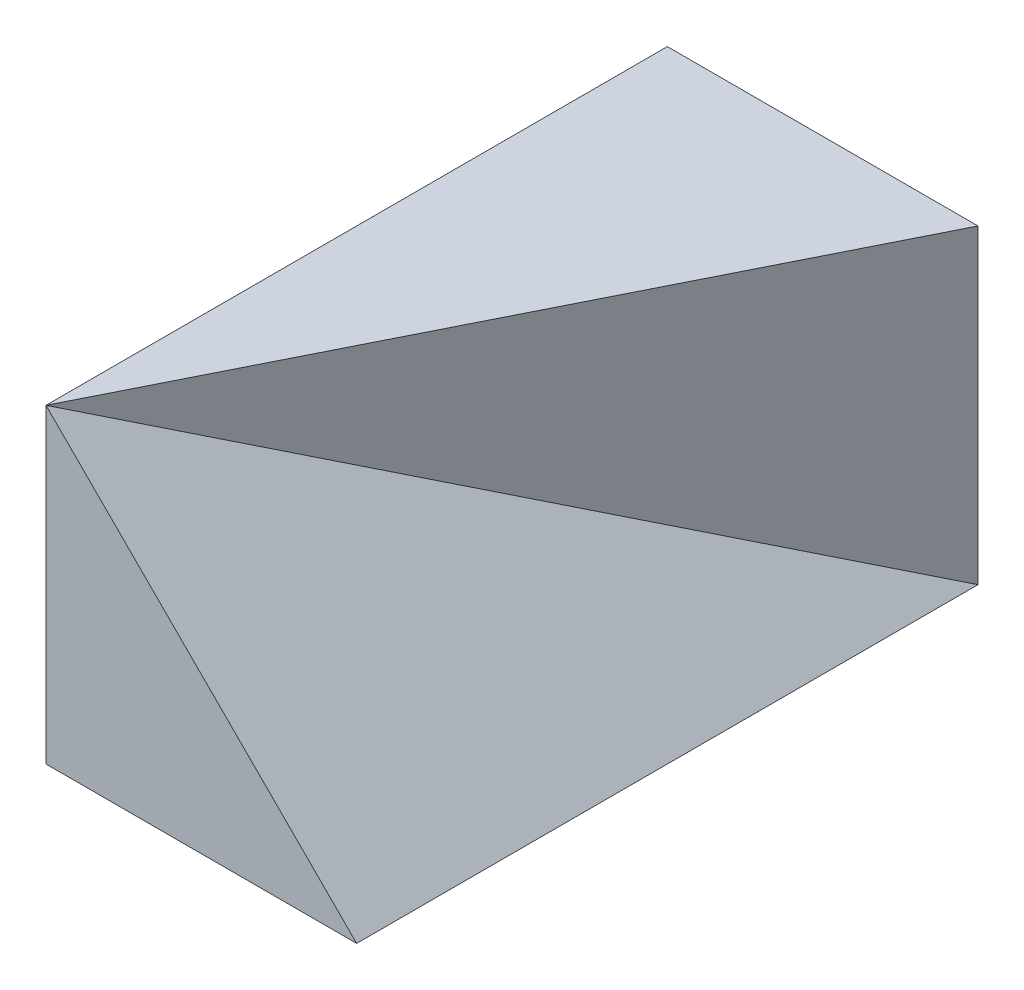
SolidWorks part; units mm, degrees
ref_plane "Front Plane" through (0, 0, 0) normal (0, 0, 1) x (1, 0, 0)
ref_plane "Top Plane" through (0, 0, 0) normal (0, 1, 0) x (1, 0, 0)
ref_plane "Right Plane" through (0, 0, 0) normal (1, 0, 0) x (0, 0, -1)
sketch "Sketch1" plane through (0, 0, 0) normal (0, 0, 1) x (1, 0, 0)
  line L1 (-25, -25) -> (25, -25)
  line L2 (-25, -25) -> (-25, 25)
  line L3 (-25, 25) -> (25, 25)
  line L4 (25, -25) -> (25, 25)
  line L5 (-25, -25) -> (25, 25) construction
  line L6 (-25, 25) -> (25, -25) construction
  point P0 (0, 0)
  dimension "D1" = 50
  dimension "D2" = 50
extrude "Boss-Extrude1" add sketch "Sketch1" along normal mid plane 100
sketch3d "3DSketch1"
  line L0 (-25, 25, 50) -> (25, -25, -50)
  line L1 (25, -25, -50) -> (25, -25, 50)
  line L2 (25, -25, 50) -> (-25, 25, 50)
  point P7 (0, 0, 0)
extrude "Cut-Extrude1" cut sketch "3DSketch1" along direction (0, 1, 0) on the side against the normal blind 100
